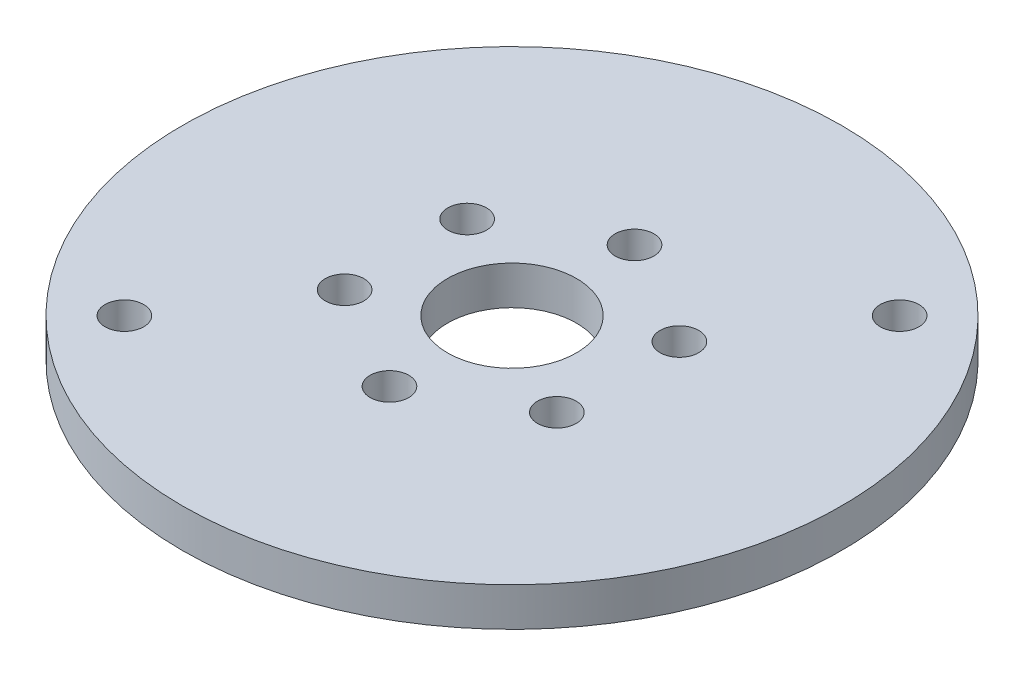
SolidWorks part; units mm, degrees
ref_plane "Front Plane" through (0, 0, 0) normal (0, 0, 1) x (1, 0, 0)
ref_plane "Top Plane" through (0, 0, 0) normal (0, 1, 0) x (1, 0, 0)
ref_plane "Right Plane" through (0, 0, 0) normal (1, 0, 0) x (0, 0, -1)
sketch "Sketch1" plane through (0, 0, 0) normal (0, 1, 0) x (1, 0, 0)
  line L0 (0, -35.0991) -> (0, 48.5715) construction
  line L1 (-15.026, -15.026) -> (15.026, 15.026) construction
  circle A0 centre (0, 0) radius 25.55
  circle A1 centre (15.026, 15.026) radius 1.5
  circle A2 centre (-15.026, -15.026) radius 1.5
  circle A3 centre (0, 0) radius 5
  circle A5 centre (0, 9.5) radius 1.5
  circle A6 centre (8.2272, 4.75) radius 1.5
  circle A7 centre (8.2272, -4.75) radius 1.5
  circle A8 centre (0, -9.5) radius 1.5
  circle A9 centre (-8.2272, -4.75) radius 1.5
  circle A10 centre (-8.2272, 4.75) radius 1.5
  point P8 (0, 0)
  point P26 (0, 0)
  dimension "D3" = 3
  dimension "D4" = 3
  dimension "D5" = 51.1
  dimension "D6" = 10
  dimension "D7" = 3
  dimension "D1" = 45
  dimension "D2" = 42.5
  dimension "D8" = 9.5
  dimension "D9" = 6
extrude "Boss-Extrude1" add sketch "Sketch1" along normal blind 3
